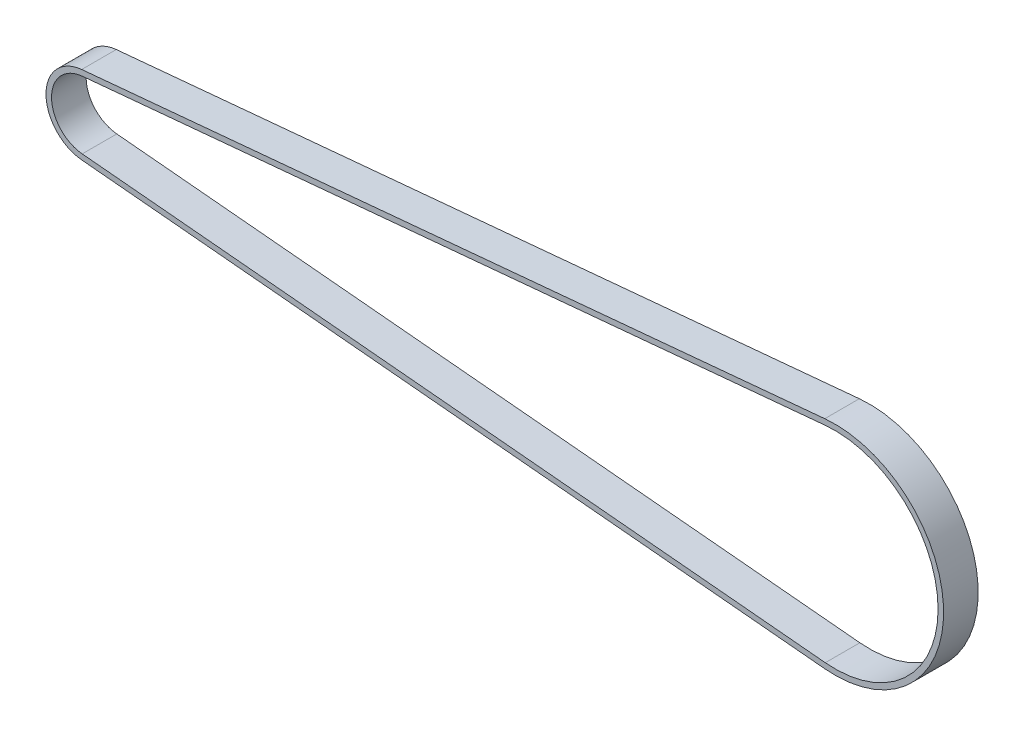
SolidWorks part; units mm, degrees
ref_plane "Front Plane" through (0, 0, 0) normal (0, 0, 1) x (1, 0, 0)
ref_plane "Top Plane" through (0, 0, 0) normal (0, 1, 0) x (1, 0, 0)
ref_plane "Right Plane" through (0, 0, 0) normal (1, 0, 0) x (0, 0, -1)
sketch "Sketch1" plane through (0, 0, 0) normal (0, 0, 1) x (1, 0, 0)
  line L0 (-0.5752, 6.1836) -> (135.9118, 18.8796)
  line L1 (-0.5752, -6.1836) -> (135.9118, -18.8796)
  line L2 (0, 0) -> (137.668, 0) construction
  arc A0 (-0.5752, -6.1836) -> (-0.5752, 6.1836) centre (0, 0) cw
  arc A1 (135.9118, 18.8796) -> (135.9118, -18.8796) centre (137.668, 0) cw
  circle A2 centre (0, 0) radius 6.2103 construction
  circle A3 centre (137.668, 0) radius 18.9611 construction
  dimension "D1" = 37.9222
  dimension "D2" = 12.4206
  dimension "D3" = 137.668
extrude "Extrude-Thin1" add sketch "Sketch1" along normal blind 6.35 thin thin type one direction wall 1.016
